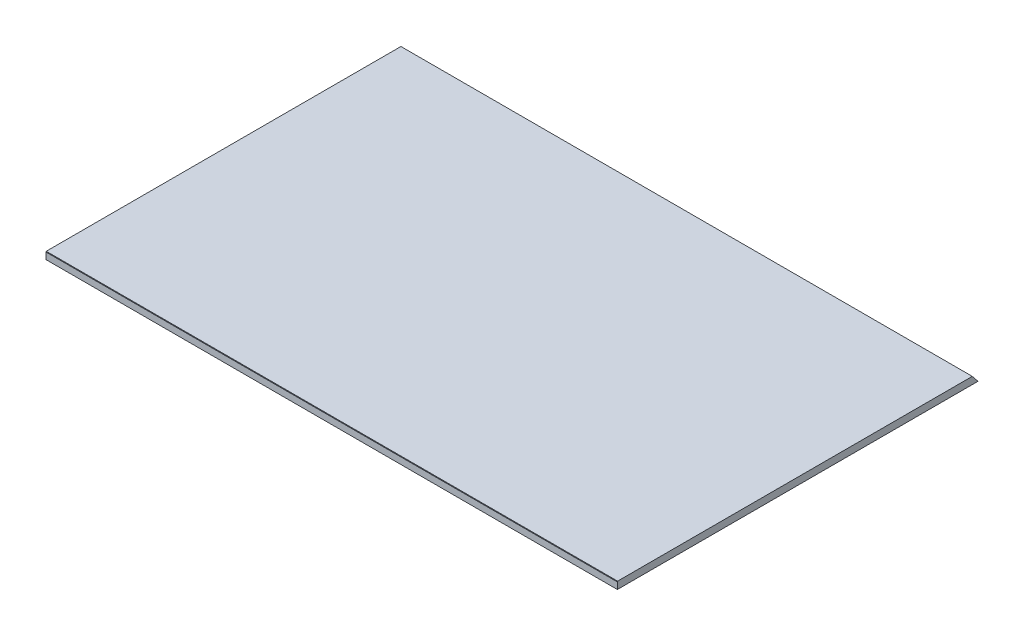
SolidWorks part; units mm, degrees
ref_plane "Front Plane" through (0, 0, 0) normal (0, 0, 1) x (1, 0, 0)
ref_plane "Top Plane" through (0, 0, 0) normal (0, 1, 0) x (1, 0, 0)
ref_plane "Right Plane" through (0, 0, 0) normal (1, 0, 0) x (0, 0, -1)
sketch "Sketch8" plane through (0, 0, 0) normal (1, 0, 0) x (0, 0, -1)
  line L3 (-88.1041, -6) -> (62.8959, -6)
  line L5 (-120, 5.68) -> (-120, 1.9989)
  line L17 (-120, 5.68) -> (-119.856, 6)
  line L25 (-120, 1.9989) -> (-106.1041, -6)
  line L26 (62.8959, -6) -> (80.8959, -3.1767)
  line L27 (-88.1041, -6) -> (-106.1041, -6)
  line L28 (80.9764, -2.9985) -> (82.7813, 0.9991)
  line L29 (80.9764, -2.9985) -> (80.8959, -3.1767)
  line L30 (78.7813, 5.9991) -> (82.7813, 0.9991)
  line L31 (-119.856, 6) -> (78.7813, 5.9991)
  point P0 (0, 0)
  point P6 (0, 0)
  dimension "D1" = 169
extrude "Boss-Extrude2" add sketch "Sketch8" along normal mid plane 320
sketch "Sketch9" plane through (0, 0, 0) normal (0, 0, 1) x (1, 0, 0)
  line L4 (0, 22.1936) -> (0, -18.3739) construction
  line L8 (-160, -6) -> (-142, -6)
  line L9 (160, -6) -> (-160, -6) construction
  line L10 (-160, 1.9989) -> (-160, -6)
  line L11 (-160, 1.9989) -> (-142, -6)
  line L12 (160, -6) -> (142, -6)
  line L13 (160, 1.9989) -> (160, -6)
  line L14 (160, 1.9989) -> (142, -6)
  dimension "D1" = 18
extrude "Cut-Extrude11" cut sketch "Sketch9" against normal through all both and the other way through all
sketch "Sketch12" plane through (0, -6, 0) normal (0, -1, 0) x (1, 0, 0)
  line L0 (-142, -62.8959) -> (-142, 106.1041) construction
  line L1 (-115, -17.8959) -> (118, -17.8959)
  line L2 (-115, -17.8959) -> (-115, -38.8959)
  line L3 (-115, -38.8959) -> (118, -38.8959)
  line L4 (118, -17.8959) -> (118, -38.8959)
  line L5 (-115, -17.8959) -> (118, -38.8959) construction
  line L6 (-115, -38.8959) -> (118, -17.8959) construction
  line L7 (142, 106.1041) -> (-142, 106.1041) construction
  point P0 (1.5, -28.3959)
  dimension "D1" = 233
  dimension "D2" = 21
  dimension "D3" = 27
  dimension "D4" = 124
extrude "Cut-Extrude12" cut sketch "Sketch12" against normal blind 2
sketch "Sketch13" plane through (0, -6, 0) normal (0, -1, 0) x (1, 0, 0)
  line L0 (142, 106.1041) -> (-142, 106.1041) construction
  line L1 (-140, 104.1041) -> (-133, 104.1041)
  line L2 (-140, 104.1041) -> (-140, 81.1041)
  line L3 (-140, 81.1041) -> (-133, 81.1041)
  line L4 (-133, 104.1041) -> (-133, 81.1041)
  line L5 (-140, 104.1041) -> (-133, 81.1041) construction
  line L6 (-140, 81.1041) -> (-133, 104.1041) construction
  line L7 (-142, -62.8959) -> (-142, 106.1041) construction
  line L8 (0, 169.9823) -> (0, -153.6761) construction
  line L13 (-188.5095, 19.0093) -> (209.6914, 19.0093) construction
  line L14 (142, -62.8959) -> (-142, -62.8959) construction
  line L15 (-140, -37.8959) -> (-133, -37.8959)
  line L16 (-140, -37.8959) -> (-140, -60.8959)
  line L17 (-140, -60.8959) -> (-133, -60.8959)
  line L18 (-133, -37.8959) -> (-133, -60.8959)
  line L19 (-140, -37.8959) -> (-133, -60.8959) construction
  line L20 (-140, -60.8959) -> (-133, -37.8959) construction
  line L21 (140, -60.8959) -> (133, -60.8959)
  line L22 (133, -37.8959) -> (133, -60.8959)
  line L23 (140, -37.8959) -> (133, -37.8959)
  line L24 (140, -37.8959) -> (140, -60.8959)
  line L25 (140, 81.1041) -> (133, 81.1041)
  line L26 (133, 104.1041) -> (133, 81.1041)
  line L27 (140, 104.1041) -> (133, 104.1041)
  line L28 (140, 104.1041) -> (140, 81.1041)
  point P0 (-136.5, 92.6041)
  point P18 (-136.5, -49.3959)
  point P25 (0, 0)
  dimension "D1" = 7
  dimension "D2" = 23
  dimension "D3" = 2
  dimension "D4" = 2
  dimension "D5" = 7
  dimension "D6" = 23
  dimension "D7" = 2
  dimension "D8" = 2
extrude "Boss-Extrude3" add sketch "Sketch13" along normal blind 2
sketch "Sketch14" plane through (-140, 0, 0) normal (-1, 0, 0) x (0, 0, 1)
  line L0 (-49.7234, -2.233) -> (-49.7234, -13.767) construction
  line L1 (-45.2234, -8) -> (-54.2234, -8)
  line L2 (-37.8959, -8) -> (-60.8959, -8) construction
  line L3 (-54.2234, -8) -> (-60.8959, -6)
  line L4 (-45.2234, -8) -> (-37.8959, -6)
  line L5 (-37.8959, -6) -> (-37.8959, -8)
  line L6 (-37.8959, -8) -> (-45.2234, -8)
  line L7 (-54.2234, -8) -> (-60.8959, -8)
  line L8 (-60.8959, -8) -> (-60.8959, -6)
  line L9 (91.8673, 0.7996) -> (91.8673, -16.5944) construction
  line L10 (87.3673, -8) -> (96.3673, -8)
  line L11 (104.1041, -8) -> (81.1041, -8) construction
  line L12 (87.3673, -8) -> (81.1041, -6)
  line L13 (96.3673, -8) -> (104.1041, -6)
  line L14 (104.1041, -6) -> (104.1041, -8)
  line L15 (104.1041, -8) -> (96.3673, -8)
  line L16 (87.3673, -8) -> (81.1041, -8)
  line L17 (81.1041, -8) -> (81.1041, -6)
  point P7 (-49.7234, -8)
  point P22 (91.8673, -8)
  point P29 (-45.2234, -8)
  line M5 (-60.8959, -6) -> (-60.8959, -8)
  line M6 (-60.8959, -8) -> (-37.8959, -8)
  dimension "D1" = 9
  dimension "D2" = 9
extrude "Cut-Extrude13" cut sketch "Sketch14" against normal through all both and the other way through all contours L3 M6 M5 | L15 L14 L13 | L17 L16 L12 | L4 L5 L6
